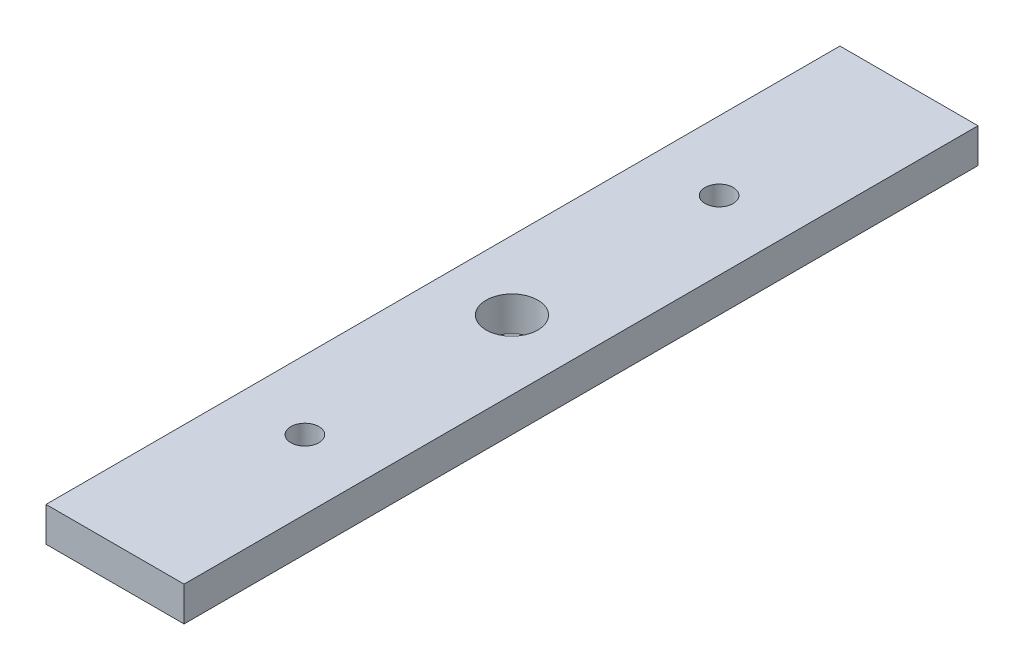
SolidWorks part; units mm, degrees
ref_plane "Front" through (0, 0, 0) normal (0, 0, 1) x (1, 0, 0)
ref_plane "Top" through (0, 0, 0) normal (0, 1, 0) x (1, 0, 0)
ref_plane "Right" through (0, 0, 0) normal (1, 0, 0) x (0, 0, -1)
sketch "Sketch1" plane through (0, 0, 0) normal (0, 1, 0) x (1, 0, 0)
  line L1 (0, 0) -> (50.8, 0)
  line L2 (0, 0) -> (0, 292.1)
  line L3 (0, 292.1) -> (50.8, 292.1)
  line L4 (50.8, 0) -> (50.8, 292.1)
  dimension "D1" = 292.1
  dimension "D2" = 50.8
extrude "Extrude1" add sketch "Sketch1" along normal blind 12.7
hole_wizard "3/8 Clearance Hole1" positions "Sketch3" profile "Sketch2" hole size "3/8" standard "Ansi Inch" end condition through all
sketch "Sketch3" plane through (0, 12.7, 0) normal (0, 1, 0) x (-1, 0, 0)
  line L0 (-50.8, 0) -> (-50.8, -292.1) construction
  line L1 (0, 0) -> (-50.8, 0) construction
  point P0 (-25.4, -69.85)
  point P1 (-25.4, -222.25)
  dimension "D1" = 25.4
  dimension "D2" = 69.85
  dimension "D3" = 152.4
sketch "Sketch2" plane through (25.4, 12.7, -69.85) normal (1, 0, 0) x (0, 0, 1)
  line L0 (0, 0) -> (0, 12.7)
  line L1 (0, 12.7) -> (5.1587, 12.7)
  line L2 (5.1587, 12.7) -> (5.1587, 0)
  line L5 (5.1587, 0) -> (0, 0)
  line L11 (0, -6.35) -> (0, 107.95) construction
  dimension "Thru Hole Dia." = 10.3175
  dimension "Thru Hole Depth" = 12.7
sketch "Sketch4" plane through (0, 0, 0) normal (0, -1, 0) x (1, 0, 0)
  circle A0 centre (25.4, -146.05) radius 9.525
  circle A1 centre (25.4, -69.85) radius 5.1587 construction
  dimension "D1" = 76.2
  dimension "D2" = 19.05
extrude "Cut-Extrude1" cut sketch "Sketch4" against normal through all
